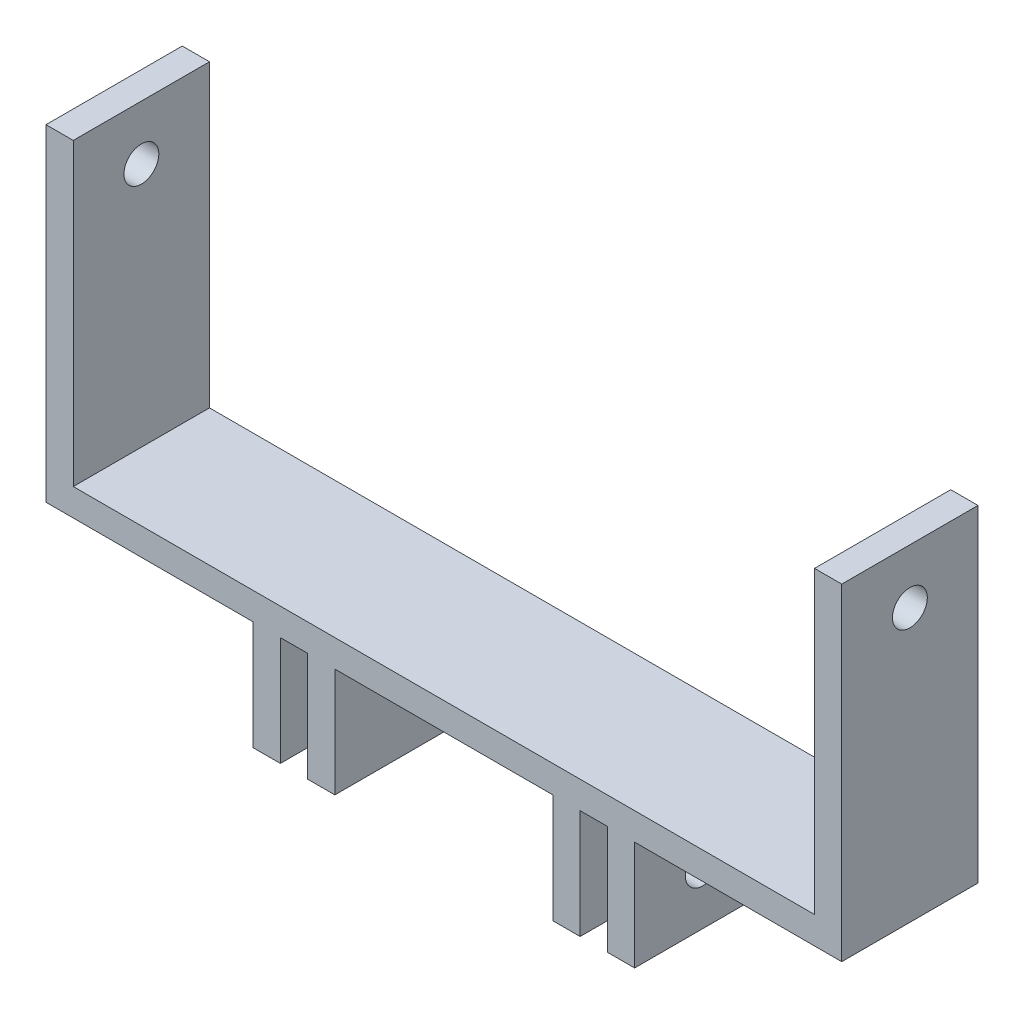
SolidWorks part; units mm, degrees
ref_plane "Front Plane" through (0, 0, 0) normal (0, 0, 1) x (1, 0, 0)
ref_plane "Top Plane" through (0, 0, 0) normal (0, 1, 0) x (1, 0, 0)
ref_plane "Right Plane" through (0, 0, 0) normal (1, 0, 0) x (0, 0, -1)
sketch "Sketch1" plane through (0, 0, 0) normal (0, 0, 1) x (1, 0, 0)
  line L0 (3.175, 3.175) -> (46.355, 3.175)
  line L1 (0, 0) -> (24.13, 0)
  line L2 (0, 0) -> (0, 38.1)
  line L3 (0, 38.1) -> (3.175, 38.1)
  line L4 (27.305, -12.7) -> (24.13, -12.7)
  line L5 (3.175, 3.175) -> (87.63, 3.175) construction
  line L6 (3.175, 3.175) -> (3.175, 34.925) construction
  line L7 (3.175, 3.175) -> (3.175, 38.1)
  line L8 (3.175, 34.925) -> (87.63, 34.925) construction
  line L9 (87.63, 3.175) -> (87.63, 34.925) construction
  line L10 (0, 0) -> (90.805, 0) construction
  line L11 (46.355, 6.35) -> (46.355, 69.133) construction
  line L12 (0, 38.1) -> (90.805, 38.1) construction
  line L13 (46.355, 0) -> (46.355, 3.175)
  line L14 (90.805, 0) -> (90.805, 38.1) construction
  line L16 (30.48, -12.7) -> (33.655, -12.7)
  line L17 (24.13, 0) -> (24.13, -12.7)
  line L19 (27.305, -12.7) -> (27.305, 0)
  line L20 (27.305, 0) -> (30.48, 0)
  line L21 (30.48, -12.7) -> (30.48, 0)
  line L29 (33.655, -12.7) -> (33.655, 0)
  line L30 (33.655, 0) -> (46.355, 0)
  point P21 (46.355, 6.35)
  point P22 (46.355, 12.7)
  point P33 (46.355, 12.7)
  dimension "D1" = 46.355
  dimension "D2" = 38.1
  dimension "D4" = 12.7
  dimension "D5" = 3.175
  dimension "D8" = 19.05
  dimension "D9" = 3.175
  dimension "D3" = 3.175
extrude "Boss-Extrude1" add sketch "Sketch1" along normal blind 15.875
sketch "Sketch3" plane through (24.13, 0, 0) normal (-1, 0, 0) x (0, 0, 1)
  line L0 (15.875, -12.7) -> (0, -12.7) construction
  circle A0 centre (7.9375, -6.35) radius 2.032
  point P4 (7.9375, -12.7)
  dimension "D2" = 4.064
  dimension "D1" = 6.35
extrude "Cut-Extrude2" cut sketch "Sketch3" against normal up to next
sketch "Sketch4" plane through (0, 0, 0) normal (-1, 0, 0) x (0, 0, 1)
  line L0 (15.875, 38.1) -> (0, 38.1) construction
  line L1 (7.9375, 38.1) -> (7.9375, -49961.9) construction
  line L2 (15.875, 0) -> (0, 0) construction
  circle A1 centre (7.9375, 31.75) radius 2.032
  point P6 (7.9375, 38.1)
  point P9 (7.9375, 0)
  dimension "D1" = 4.064
  dimension "D3" = 6.35
extrude "Cut-Extrude3" cut sketch "Sketch4" against normal up to next
ref_plane "Plane1" through (46.355, 0, 0) normal (1, 0, 0) x (0, 0, -1)
mirror "Mirror2" about plane through (46.355, 0, 0) normal (1, 0, 0) of "Cut-Extrude2", "Boss-Extrude1", "Cut-Extrude3"
